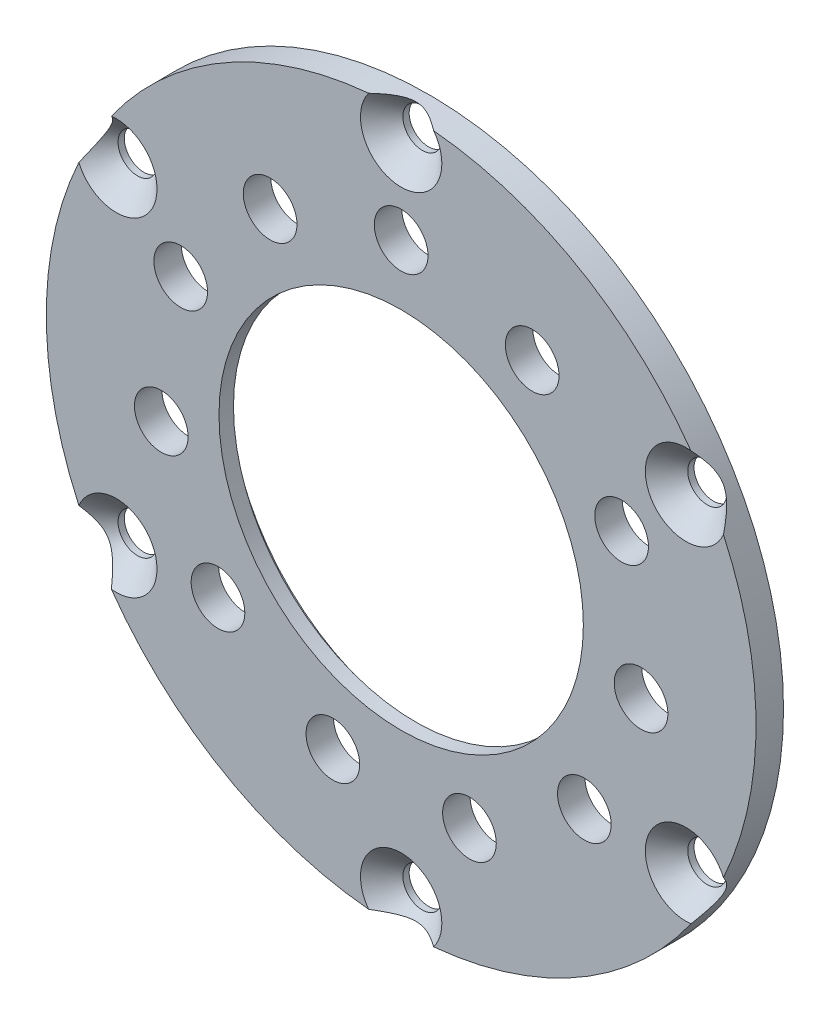
SolidWorks part; units mm, degrees
ref_plane "Front Plane" through (0, 0, 0) normal (1, 0, 0) x (0, 1, 0)
ref_plane "Top Plane" through (0, 0, 0) normal (0, 0, 1) x (0, 1, 0)
ref_plane "Right Plane" through (0, 0, 0) normal (0, 1, 0) x (-1, 0, 0)
sketch "Sketch1" plane through (0, 0, 0) normal (0, 0, 1) x (0, 1, 0)
  circle A0 centre (0, 0) radius 41
  circle A1 centre (0, 0) radius 21.05
  dimension "D1" = 82
  dimension "D2" = 42.1
extrude "Boss-Extrude1" add sketch "Sketch1" along normal blind 3.175
sketch "Sketch2" plane through (0, 0, 0) normal (0, 0, -1) x (1, 0, 0)
  circle A0 centre (0, 0) radius 23
  dimension "D1" = 46
extrude "Cut-Extrude1" cut sketch "Sketch2" against normal blind 1.5 contours A0
sketch "Sketch3" plane through (0, 0, 3.175) normal (0, 0, 1) x (1, 0, 0)
  circle A0 centre (0, 38) radius 2.1
  circle A1 centre (32.909, 19) radius 2.1
  circle A2 centre (32.909, -19) radius 2.1
  circle A3 centre (0, -38) radius 2.1
  circle A4 centre (-32.909, -19) radius 2.1
  circle A5 centre (-32.909, 19) radius 2.1
  point P0 (0, 38)
  point P2 (32.909, 19)
  point P7 (32.909, -19)
  point P9 (0, -38)
  point P11 (-32.909, -19)
  point P13 (-32.909, 19)
  point P15 (0, 0)
  dimension "D1" = 4.2
  dimension "D2" = 38
  dimension "D3" = 6
hole_wizard "CSK for M4 Countersunk Flat Head Screw1" positions "Sketch3" profile "Sketch4" countersink size "M4" standard "ISO" end condition through all
sketch "Sketch4" plane through (0, 38, 3.175) normal (1, 0, 0) x (0, -1, 0)
  line L0 (0, 0) -> (0, 3.175)
  line L1 (0, 3.175) -> (2.25, 3.175)
  line L2 (2.25, 3.175) -> (2.25, 2.45)
  line L3 (2.25, 2.45) -> (4.7, 0)
  line L5 (4.7, 0) -> (0, 0)
  line L6 (-2.25, 2.45) -> (-4.7, 0) construction
  line L11 (0, -6.35) -> (0, 107.95) construction
  dimension "Thru Hole Dia." = 4.5
  dimension "Thru Hole Depth" = 3.175
  dimension "Near C'Sink Dia." = 9.4
  dimension "Near C'Sink Angle" = 90
sketch "Sketch5" plane through (0, 0, 3.175) normal (0, 0, 1) x (1, 0, 0)
  circle A0 centre (0, 28) radius 3.1
  circle A1 centre (15.1379, 23.5551) radius 3.1
  circle A2 centre (25.4697, 11.6316) radius 3.1
  circle A3 centre (27.715, -3.9848) radius 3.1
  circle A4 centre (21.161, -18.3361) radius 3.1
  circle A5 centre (7.8885, -26.8658) radius 3.1
  circle A6 centre (-7.8885, -26.8658) radius 3.1
  circle A7 centre (-21.161, -18.3361) radius 3.1
  circle A8 centre (-27.715, -3.9848) radius 3.1
  circle A9 centre (-25.4697, 11.6316) radius 3.1
  circle A10 centre (-15.1379, 23.5551) radius 3.1
  point P2 (16.2019, 26.2787)
  point P4 (0, 0)
  point P5 (0, 0)
  point P26 (0, 0)
  point P27 (21.161, -18.3361)
  dimension "D1" = 6.2
  dimension "D2" = 28
  dimension "D3" = 11
extrude "Cut-Extrude2" cut sketch "Sketch5" against normal through all contours A8 | A7 | A6 | A5 | A4 | A3 | A2 | A1 | A0 | A10 | A9
